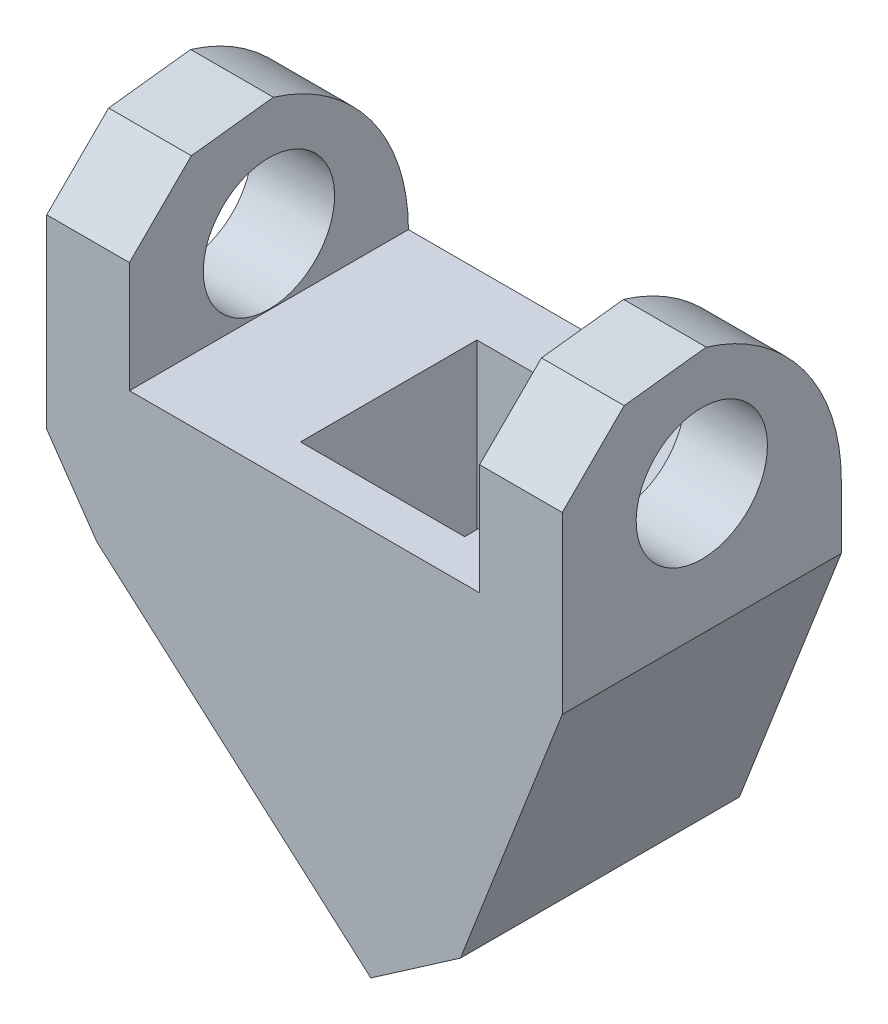
SolidWorks part; units mm, degrees
ref_plane "Plan de face" through (0, 0, 0) normal (0, 0, 1) x (1, 0, 0)
ref_plane "Plan de dessus" through (0, 0, 0) normal (0, 1, 0) x (1, 0, 0)
ref_plane "Plan de droite" through (0, 0, 0) normal (1, 0, 0) x (0, 0, -1)
sketch "Sketch1" plane through (0, 0, 0) normal (0, 0, 1) x (1, 0, 0)
  line L0 (0, 0) -> (0, 11.1)
  line L1 (0, 11.1) -> (5.04, 11.1)
  line L2 (5.04, 11.1) -> (5.04, -3.9)
  line L3 (5.04, -3.9) -> (-1.1665, -19.86)
  line L4 (-1.1665, -19.86) -> (-6.6262, -23.6391)
  line L5 (-6.6262, -23.6391) -> (-23.3193, -8.9738)
  line L6 (-23.3193, -8.9738) -> (-26.3756, -4.5584)
  line L7 (-26.3756, -4.5584) -> (-26.3756, 11.1)
  line L8 (-26.3756, 11.1) -> (-21.3356, 11.1)
  line L9 (-21.3356, 11.1) -> (-21.3356, 0)
  line L10 (-21.3356, 0) -> (0, 0)
  point P3 (5.04, -5.7902)
  point P13 (1.5196, -13.8501)
  point P14 (-17.2868, -8.5694)
  point P15 (-4.039, -19.316)
  dimension "D1" = 5.04
  dimension "D2" = 5.04
  dimension "D3" = 15
  dimension "D4" = 158.75
  dimension "D5" = 15.96
  dimension "D6" = 6.64
  dimension "D7" = 145.94
  dimension "D8" = 104.01
  dimension "D9" = 22.22
  dimension "D10" = 5.37
  dimension "D11" = 21.3356
  dimension "D12" = 11.1
extrude "Boss-Extrude1" add sketch "Sketch1" along normal blind 17
sketch "Sketch2" plane through (0, 0, 0) normal (-1, 0, 0) x (0, 0, 1)
  line L2 (17, 0) -> (17, 6.76)
  line L3 (17, 11.1) -> (17, 0) construction
  line L4 (17, 6.76) -> (13.2281, 10.5122)
  line L6 (13.2281, 10.5122) -> (8.2281, 11.1)
  line L7 (17, 11.1) -> (0, 11.1) construction
  line L9 (0, 11.1) -> (0, 0) construction
  line L10 (17, 6.76) -> (17, 12.8811)
  line L12 (0, 12.8811) -> (0, 0)
  line L13 (0, 12.8811) -> (17, 12.8811)
  arc A0 (8.2281, 11.1) -> (0, 0) centre (11.6012, 0) ccw
  line M6 (0, 11.1) -> (0, 0)
  line M8 (17, 0) -> (17, 11.1)
  line M9 (17, 11.1) -> (0, 11.1)
  dimension "D1" = 6.76
  dimension "D2" = 134.85
  dimension "D3" = 5
  dimension "D4" = 10
extrude "Cut-Extrude1" cut sketch "Sketch2" against normal mid plane 62 contours L13 L12 L10 M9 | A0 M9 M6 | L6 L4 M8 M9
ref_plane "Plane1" through (0, 0, 7) normal (0, 0, 1) x (1, 0, 0)
sketch "Sketch3" plane through (-14.6075, -16.6273, 0) normal (-0.66, -0.7513, 0) x (-0.7513, 0.66, 0)
  line L0 (-10.6238, -17) -> (-10.6238, 0) construction
  line L1 (2.8662, -3.74) -> (-6.6038, -3.74)
  line L2 (2.8662, -3.74) -> (2.8662, -14.49)
  line L3 (2.8662, -14.49) -> (-6.6038, -14.49)
  line L4 (-6.6038, -3.74) -> (-6.6038, -14.49)
  line L5 (11.5962, 0) -> (-10.6238, 0) construction
  dimension "D1" = 10.75
  dimension "D2" = 9.47
  dimension "D3" = 4.02
  dimension "D4" = 3.74
sketch "Sketch5" plane through (0, 0, 7) normal (0, 0, 1) x (1, 0, 0)
  line L0 (-11.0796, -19.7266) -> (-3.7738, -14.2012)
  line L1 (-16.7608, -14.7356) -> (-9.6463, -20.9859) construction
  dimension "D1" = 101.6
  dimension "D2" = 9.16
sweep "Cut-Sweep1" cut profiles "Sketch3" path "Sketch5"
sketch "Sketch6" plane through (0, 0, 0) normal (0, 1, 0) x (1, 0, 0)
  line L0 (5.04, -13.2281) -> (5.04, -8.2281) construction
  line L1 (-3.42, -14.49) -> (-13.42, -14.49)
  line L2 (-3.42, -14.49) -> (-3.42, -3.74)
  line L3 (-3.42, -3.74) -> (-13.42, -3.74)
  line L4 (-13.42, -14.49) -> (-13.42, -3.74)
  line L5 (0, 0) -> (-21.3356, 0) construction
  dimension "D1" = 10.75
  dimension "D2" = 10
  dimension "D3" = 8.46
  dimension "D4" = 3.74
extrude "Cut-Extrude2" cut sketch "Sketch6" against normal up to surface (23.8399 mm away)
ref_plane "Plane2" through (-10.6678, 0, 0) normal (-1, 0, 0) x (0, 0, 1)
sketch "Sketch7" plane through (-10.6678, 0, 0) normal (-1, 0, 0) x (0, 0, 1)
  line L0 (17, -4.5584) -> (0, -4.5584) construction
  line L1 (17, 6.76) -> (17, -4.5584) construction
  circle A0 centre (8.5, 4.0416) radius 4
  dimension "D2" = 8
  dimension "D1" = 8.6
  dimension "D3" = 8.5
extrude "Cut-Extrude3" cut sketch "Sketch7" against normal mid plane 62
